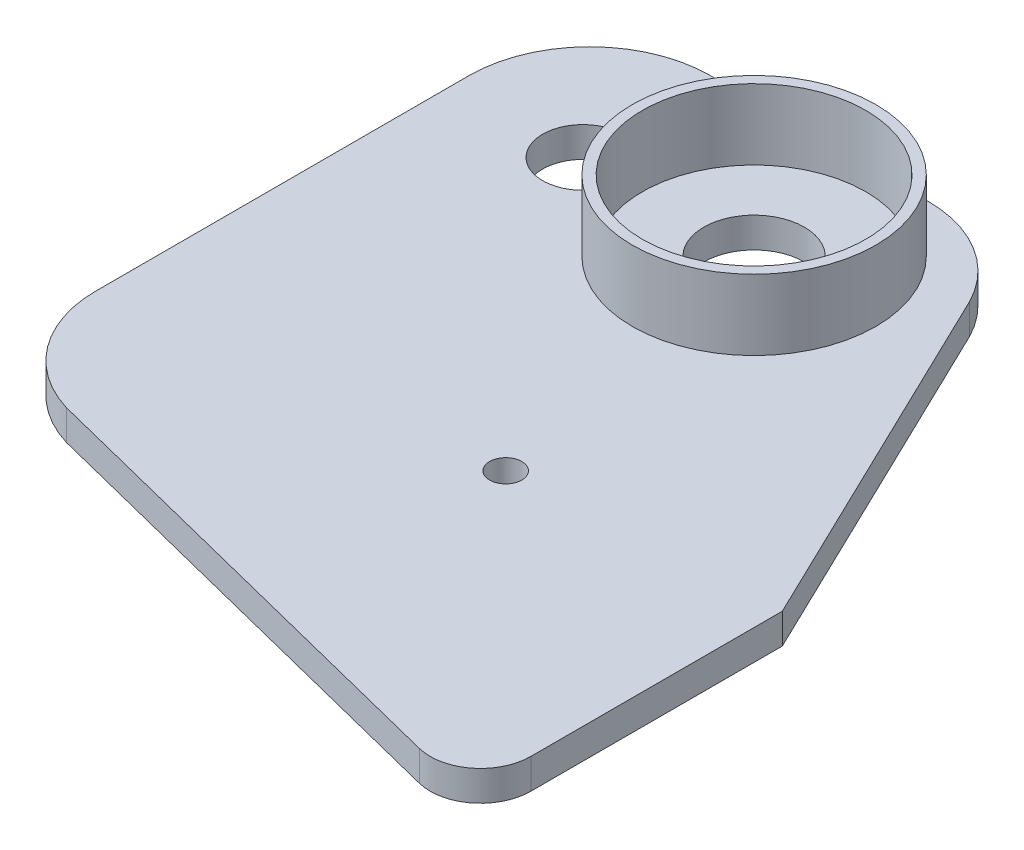
SolidWorks part; units mm, degrees
ref_plane "Ön Düzlem" through (0, 0, 0) normal (0, 0, 1) x (1, 0, 0)
ref_plane "Üst Düzlem" through (0, 0, 0) normal (0, 1, 0) x (1, 0, 0)
ref_plane "Sağ Düzlem" through (0, 0, 0) normal (1, 0, 0) x (0, 0, -1)
sketch "Çizim1" plane through (0, 0, 0) normal (0, 1, 0) x (1, 0, 0)
  line L7 (50.7602, 37.6146) -> (68.0843, 1.7039)
  line L8 (61.8647, -28.1355) -> (14.9999, -16.3429)
  line L9 (18.4349, 44.2163) -> (40.0427, 44.2166)
  line L10 (6.4354, 1.691) -> (6.4351, 32.2162)
  line L11 (6.4354, 1.691) -> (6.4355, -4.8454)
  line L12 (68.0843, 1.7039) -> (68.0848, -23.2865)
  circle A7 centre (42.2605, 0.0416) radius 1.6
  circle A8 centre (19.1355, 30.8419) radius 4
  circle A9 centre (36.1355, 30.846) radius 5
  arc A10 (40.0427, 44.2166) -> (50.7602, 37.6146) centre (40.0429, 32.2166) cw
  arc A11 (6.4351, 32.2162) -> (18.4349, 44.2163) centre (18.4351, 32.2163) cw
  arc A12 (14.9999, -16.3429) -> (6.4355, -4.8454) centre (18.4355, -4.8452) cw
  arc A13 (68.0848, -23.2865) -> (61.8647, -28.1355) centre (63.0848, -23.2866) cw
extrude "Yükseklik-Ekstrüzyon1" add sketch "Çizim1" along normal blind 3
sketch "Çizim2" plane through (0, 3, 0) normal (0, 1, 0) x (1, 0, 0)
  circle A0 centre (36.1355, 30.846) radius 11.1
  circle A1 centre (36.1355, 30.846) radius 12.1
extrude "Yükseklik-Ekstrüzyon2" add sketch "Çizim2" along normal blind 7
sketch "Çizim3" plane through (0, 3, 0) normal (0, 1, 0) x (1, 0, 0)
  line L0 (29.2388, 44.2165) -> (29.2388, -6.9178) construction
  line L1 (40.0427, 44.2166) -> (18.4349, 44.2163) construction
  circle A0 centre (22.2388, 40.2164) radius 1.6
  dimension "D1" = 3.2
  dimension "D2" = 4
  dimension "D3" = 7
extrude "Kes-Ekstrüzyon1" cut sketch "Çizim3" against normal through all
